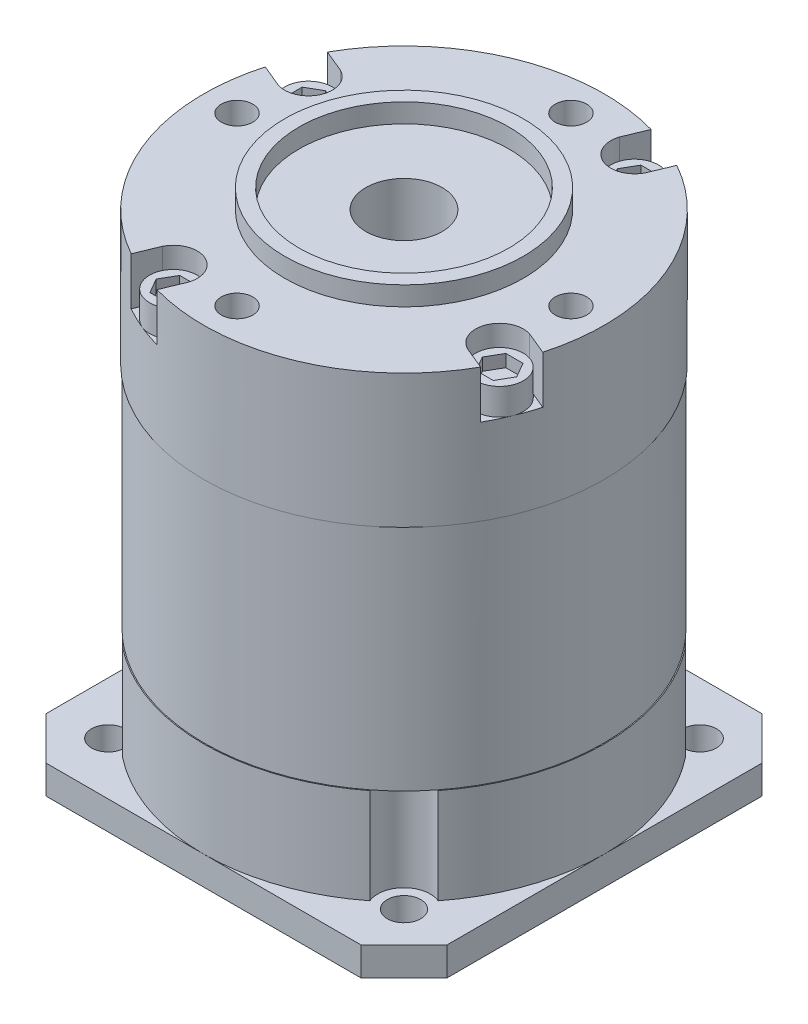
SolidWorks part; units mm, degrees
ref_plane "前视基准面" through (0, 0, 0) normal (0, 0, 1) x (1, 0, 0)
ref_plane "上视基准面" through (0, 0, 0) normal (0, 1, 0) x (1, 0, 0)
ref_plane "右视基准面" through (0, 0, 0) normal (1, 0, 0) x (0, 0, -1)
other "Configuration Table"
sketch "草图1" plane through (0, 0, 0) normal (0, 1, 0) x (1, 0, 0)
  line L1 (-21, 21) -> (21, 21)
  line L2 (-21, 21) -> (-21, -21)
  line L3 (-21, -21) -> (21, -21)
  line L4 (21, 21) -> (21, -21)
  line L5 (-21, 21) -> (21, -21) construction
  line L6 (-21, -21) -> (21, 21) construction
  point P0 (0, 0)
  dimension "D1" = 42
  dimension "D2" = 42
extrude "凸台-拉伸1" add sketch "草图1" along normal blind 3
sketch "草图2" plane through (0, 0, 0) normal (0, 1, 0) x (1, 0, 0)
  line L0 (-1000, 0) -> (49000, 0) construction
  line L1 (0, -1000) -> (0, 49000) construction
  line L2 (-21, 21) -> (-21, 16.5)
  line L3 (-21, 21) -> (-21, -21) construction
  line L4 (-21, 16.5) -> (-16.5, 21)
  line L5 (21, 21) -> (-21, 21) construction
  line L6 (-16.5, 21) -> (-21, 21)
  line L7 (16.5, 21) -> (21, 21)
  line L8 (21, 16.5) -> (16.5, 21)
  line L9 (21, 21) -> (21, 16.5)
  line L10 (21, -21) -> (21, -16.5)
  line L11 (21, -16.5) -> (16.5, -21)
  line L12 (16.5, -21) -> (21, -21)
  line L13 (-16.5, -21) -> (-21, -21)
  line L14 (-21, -16.5) -> (-16.5, -21)
  line L15 (-21, -21) -> (-21, -16.5)
  dimension "D1" = 4.5
  dimension "D2" = 4.5
extrude "切除-拉伸1" cut sketch "草图2" against normal up to surface (3 mm away) from surface at 3 up to face at (0, 0, 0) starting at face at (0, 3, 0)
sketch "草图3" plane through (0, 0, 0) normal (0, 1, 0) x (1, 0, 0)
  circle A0 centre (0, 0) radius 21
  dimension "D1" = 42
extrude "凸台-拉伸2" add sketch "草图3" along normal blind 51
sketch "草图5" plane through (0, 0, 0) normal (0, 1, 0) x (1, 0, 0)
  line L1 (-15.5, 15.5) -> (15.5, 15.5) construction
  line L2 (-15.5, 15.5) -> (-15.5, -15.5) construction
  line L3 (-15.5, -15.5) -> (15.5, -15.5) construction
  line L4 (15.5, 15.5) -> (15.5, -15.5) construction
  line L5 (-15.5, 15.5) -> (15.5, -15.5) construction
  line L6 (-15.5, -15.5) -> (15.5, 15.5) construction
  circle A0 centre (-15.5, 15.5) radius 1.75
  circle A1 centre (15.5, 15.5) radius 1.75
  circle A2 centre (-15.5, -15.5) radius 1.75
  circle A3 centre (15.5, -15.5) radius 1.75
  point P0 (0, 0)
  dimension "D3" = 3.5
  dimension "D4" = 3.5
  dimension "D5" = 3.5
  dimension "D6" = 3.5
  dimension "D1" = 31
  dimension "D2" = 31
extrude "切除-拉伸3" cut sketch "草图5" along normal up to surface (3 mm away) from surface at 0 up to face at (15.7123, 3, 15.7123) starting at face at (0, 0, 0)
sketch "草图7" plane through (0, 0, 0) normal (0, 1, 0) x (1, 0, 0)
  circle A0 centre (-15.5, 15.5) radius 2.75
  circle A1 centre (15.5, 15.5) radius 2.75
  circle A2 centre (-15.5, -15.5) radius 2.75
  circle A3 centre (15.5, -15.5) radius 2.75
  dimension "D1" = 5.5
  dimension "D2" = 5.5
  dimension "D3" = 5.5
  dimension "D4" = 5.5
extrude "切除-拉伸4" cut sketch "草图7" along normal blind 10 from surface at 3 starting at face at (15.2941, 3, -15.2941)
sketch "草图8" plane through (0, 0, 0) normal (0, 1, 0) x (1, 0, 0)
  circle A0 centre (0, 0) radius 20.9
  circle A1 centre (0, 0) radius 21
  dimension "D1" = 41.8
  dimension "D2" = 42
extrude "切除-拉伸5" cut sketch "草图8" along normal blind 24 from surface at 13 starting at face at (14.2023, 13, 14.2023)
sketch "草图9" plane through (0, 0, 0) normal (0, 1, 0) x (1, 0, 0)
  circle A0 centre (0, 0) radius 12.5
  dimension "D1" = 25
extrude "凸台-拉伸3" add sketch "草图9" along normal blind 2 from surface at 51 starting at face at (0, 51, 21)
sketch "草图11" plane through (0, 0, 0) normal (0, 1, 0) x (1, 0, 0)
  line L0 (-1000, 0) -> (49000, 0) construction
  line L1 (0, -1000) -> (0, 49000) construction
  circle A0 centre (0, 0) radius 17.5 construction
  circle A1 centre (-17.5, 0) radius 2
  circle A2 centre (0, -17.5) radius 2
  circle A3 centre (17.5, 0) radius 2
  circle A4 centre (0, 17.5) radius 2
  point P7 (0, 17.5)
  point P8 (-17.5, 0)
  point P9 (17.5, 0)
  point P10 (0, -17.5)
  point P11 (22.5067, -42.5527)
  dimension "D1" = 35
  dimension "D2" = 4
  dimension "D3" = 4
  dimension "D4" = 4
  dimension "D5" = 4
sketch "草图16" plane through (0, 0, 0) normal (0, 1, 0) x (1, 0, 0)
  circle A0 centre (0, 0) radius 11
  dimension "D1" = 22
extrude "切除-拉伸6" cut sketch "草图16" against normal up to surface (2 mm away) from surface at 53 up to face at (0, 51, 12.5) starting at face at (0, 53, 12.5)
sketch "草图17" plane through (0, 0, 0) normal (0, 1, 0) x (1, 0, 0)
  line L0 (-1000, 0) -> (49000, 0) construction
  line L1 (0, -1000) -> (0, 49000) construction
  line L2 (0, 0) -> (19134.1716, 46193.9766) construction
  line L3 (0, 0) -> (46193.9766, -19134.1716) construction
  line L4 (-18.3096, 10.2839) -> (-15.9812, 9.3194)
  line L5 (-20.2187, 5.675) -> (-17.8902, 4.7106)
  line L6 (18.3096, -10.2839) -> (15.9812, -9.3194)
  line L7 (20.2187, -5.675) -> (17.8902, -4.7106)
  line L8 (-4.7106, -17.8902) -> (-5.675, -20.2187)
  line L9 (-9.3194, -15.9812) -> (-10.2839, -18.3096)
  line L10 (4.7106, 17.8902) -> (5.675, 20.2187)
  line L11 (9.3194, 15.9812) -> (10.2839, 18.3096)
  arc A1 (-18.2024, 4.8399) -> (-16.2933, 9.4487) centre (-17.0918, 7.0796) ccw
  arc A2 (-4.8399, -18.2024) -> (-9.4487, -16.2933) centre (-7.0796, -17.0918) ccw
  arc A3 (18.2024, -4.8399) -> (16.2933, -9.4487) centre (17.0918, -7.0796) ccw
  arc A4 (4.8399, 18.2024) -> (9.4487, 16.2933) centre (7.0796, 17.0918) ccw
  circle A5 centre (0, 0) radius 21 construction
  arc A6 (-10.2839, -18.3096) -> (-5.675, -20.2187) centre (0, 0) ccw
  arc A7 (16.5312, -12.9507) -> (21, 0) centre (0, 0) ccw construction
  circle A8 centre (0, 0) radius 18.5 construction
  arc A9 (-18.3096, 10.2839) -> (-20.2187, 5.675) centre (0, 0) ccw
  arc A10 (10.2839, 18.3096) -> (5.675, 20.2187) centre (0, 0) ccw
  arc A11 (18.3096, -10.2839) -> (20.2187, -5.675) centre (0, 0) ccw
  point P12 (7.0796, 17.0918)
  point P13 (17.0918, -7.0796)
  point P14 (-7.0796, -17.0918)
  point P15 (-17.0918, 7.0796)
  dimension "D3" = 37
  dimension "D1" = 22.5
  dimension "D2" = 22.5
extrude "切除-拉伸7" cut sketch "草图17" against normal blind 5 from surface at 51 contours L6 A11 L7 A3 | L9 A6 L8 A2 | L4 A9 L5 A1 | L11 A10 L10 A4 starting at face at (0, 51, 12.5)
sketch "草图18" plane through (0, 0, 0) normal (0, 1, 0) x (1, 0, 0)
  line L1 (-15.5329, 7.9796) -> (-17.0918, 8.8796)
  line L2 (-17.0918, 8.8796) -> (-18.6506, 7.9796)
  line L3 (-18.6506, 7.9796) -> (-18.6506, 6.1796)
  line L4 (-18.6506, 6.1796) -> (-17.0918, 5.2796)
  line L5 (-17.0918, 5.2796) -> (-15.5329, 6.1796)
  line L6 (-15.5329, 6.1796) -> (-15.5329, 7.9796)
  line L7 (7.9796, 15.5329) -> (8.8796, 17.0918)
  line L8 (8.8796, 17.0918) -> (7.9796, 18.6506)
  line L9 (7.9796, 18.6506) -> (6.1796, 18.6506)
  line L10 (6.1796, 18.6506) -> (5.2796, 17.0918)
  line L11 (5.2796, 17.0918) -> (6.1796, 15.5329)
  line L12 (6.1796, 15.5329) -> (7.9796, 15.5329)
  line L13 (18.8918, -7.0796) -> (17.9918, -5.5208)
  line L14 (17.9918, -5.5208) -> (16.1918, -5.5208)
  line L15 (16.1918, -5.5208) -> (15.2918, -7.0796)
  line L16 (15.2918, -7.0796) -> (16.1918, -8.6385)
  line L17 (16.1918, -8.6385) -> (17.9918, -8.6385)
  line L18 (17.9918, -8.6385) -> (18.8918, -7.0796)
  line L19 (-6.1796, -18.6506) -> (-5.2796, -17.0918)
  line L20 (-5.2796, -17.0918) -> (-6.1796, -15.5329)
  line L21 (-6.1796, -15.5329) -> (-7.9796, -15.5329)
  line L22 (-7.9796, -15.5329) -> (-8.8796, -17.0918)
  line L23 (-8.8796, -17.0918) -> (-7.9796, -18.6506)
  line L24 (-7.9796, -18.6506) -> (-6.1796, -18.6506)
  circle A0 centre (-17.0918, 7.0796) radius 2.5
  circle A1 centre (-7.0796, -17.0918) radius 2.5
  circle A2 centre (17.0918, -7.0796) radius 2.5
  circle A3 centre (7.0796, 17.0918) radius 2.5
  circle A4 centre (-17.0918, 7.0796) radius 1.5588 construction
  circle A5 centre (7.0796, 17.0918) radius 1.5588 construction
  circle A6 centre (17.0918, -7.0796) radius 1.5588 construction
  circle A7 centre (-7.0796, -17.0918) radius 1.5588 construction
  dimension "D1" = 1.8
  dimension "D2" = 1.8
  dimension "D3" = 1.8
  dimension "D4" = 1.8
extrude "凸台-拉伸5" add sketch "草图18" along normal blind 2.8 from surface at 46 starting at face at (-7.2884, 46, 17.5958)
sketch "草图19" plane through (0, 0, 0) normal (0, 1, 0) x (1, 0, 0)
  circle A0 centre (0, 0) radius 4
  dimension "D1" = 8
extrude "切除-拉伸8" cut sketch "草图19" along normal up to surface (51 mm away) from surface at 0 up to face at (0, 51, 11) starting at face at (15.5, 0, -13.75)
sketch "草图20" plane through (0, 0, 0) normal (0, 1, 0) x (1, 0, 0)
  line L0 (7.9796, 18.6506) -> (6.1796, 18.6506) construction
  line L1 (6.1796, 18.6506) -> (5.2796, 17.0918) construction
  line L2 (5.2796, 17.0918) -> (6.1796, 15.5329) construction
  line L3 (6.1796, 15.5329) -> (7.9796, 15.5329) construction
  line L4 (7.9796, 15.5329) -> (8.8796, 17.0918) construction
  line L5 (8.8796, 17.0918) -> (7.9796, 18.6506) construction
  line L6 (16.1918, -5.5208) -> (15.2918, -7.0796) construction
  line L7 (15.2918, -7.0796) -> (16.1918, -8.6385) construction
  line L8 (16.1918, -8.6385) -> (17.9918, -8.6385) construction
  line L9 (17.9918, -8.6385) -> (18.8918, -7.0796) construction
  line L10 (18.8918, -7.0796) -> (17.9918, -5.5208) construction
  line L11 (17.9918, -5.5208) -> (16.1918, -5.5208) construction
  line L12 (-6.1796, -15.5329) -> (-7.9796, -15.5329) construction
  line L13 (-7.9796, -15.5329) -> (-8.8796, -17.0918) construction
  line L14 (-8.8796, -17.0918) -> (-7.9796, -18.6506) construction
  line L15 (-7.9796, -18.6506) -> (-6.1796, -18.6506) construction
  line L16 (-6.1796, -18.6506) -> (-5.2796, -17.0918) construction
  line L17 (-5.2796, -17.0918) -> (-6.1796, -15.5329) construction
  line L18 (-18.6506, 7.9796) -> (-18.6506, 6.1796) construction
  line L19 (-18.6506, 6.1796) -> (-17.0918, 5.2796) construction
  line L20 (-17.0918, 5.2796) -> (-15.5329, 6.1796) construction
  line L21 (-15.5329, 6.1796) -> (-15.5329, 7.9796) construction
  line L22 (-15.5329, 7.9796) -> (-17.0918, 8.8796) construction
  line L23 (-17.0918, 8.8796) -> (-18.6506, 7.9796) construction
  line L24 (7.9796, 18.6506) -> (6.1796, 18.6506)
  line L25 (6.1796, 18.6506) -> (5.2796, 17.0918)
  line L26 (5.2796, 17.0918) -> (6.1796, 15.5329)
  line L27 (6.1796, 15.5329) -> (7.9796, 15.5329)
  line L28 (7.9796, 15.5329) -> (8.8796, 17.0918)
  line L29 (8.8796, 17.0918) -> (7.9796, 18.6506)
  line L30 (16.1918, -5.5208) -> (15.2918, -7.0796)
  line L31 (15.2918, -7.0796) -> (16.1918, -8.6385)
  line L32 (16.1918, -8.6385) -> (17.9918, -8.6385)
  line L33 (17.9918, -8.6385) -> (18.8918, -7.0796)
  line L34 (18.8918, -7.0796) -> (17.9918, -5.5208)
  line L35 (17.9918, -5.5208) -> (16.1918, -5.5208)
  line L36 (-6.1796, -15.5329) -> (-7.9796, -15.5329)
  line L37 (-7.9796, -15.5329) -> (-8.8796, -17.0918)
  line L38 (-8.8796, -17.0918) -> (-7.9796, -18.6506)
  line L39 (-7.9796, -18.6506) -> (-6.1796, -18.6506)
  line L40 (-6.1796, -18.6506) -> (-5.2796, -17.0918)
  line L41 (-5.2796, -17.0918) -> (-6.1796, -15.5329)
  line L42 (-18.6506, 7.9796) -> (-18.6506, 6.1796)
  line L43 (-18.6506, 6.1796) -> (-17.0918, 5.2796)
  line L44 (-17.0918, 5.2796) -> (-15.5329, 6.1796)
  line L45 (-15.5329, 6.1796) -> (-15.5329, 7.9796)
  line L46 (-15.5329, 7.9796) -> (-17.0918, 8.8796)
  line L47 (-17.0918, 8.8796) -> (-18.6506, 7.9796)
extrude "凸台-拉伸6" add sketch "草图20" along normal blind 1.5 from surface at 46 starting at face at (-17.0918, 46, -7.0796)
sketch "草图21" plane through (0, 0, 0) normal (0, 1, 0) x (1, 0, 0)
  circle A0 centre (0, 0) radius 12.5
  dimension "D1" = 25
extrude "切除-拉伸9" cut sketch "草图21" along normal blind 3
hole_wizard "M4 螺纹孔1" positions "草图24" profile "草图25" tap size "M4" standard "ISO"
sketch "草图24" plane through (0, 51, 0) normal (0, 1, 0) x (1, 0, 0)
  point P0 (0, 17.5)
  point P3 (-17.5, 0)
  point P6 (17.5, 0)
  point P9 (0, -17.5)
sketch "草图25" plane through (0, 51, -17.5) normal (1, 0, 0) x (0, 0, 1)
  line L0 (0, 0) -> (0, 11.0914)
  line L1 (0, 11.0914) -> (1.65, 10.1)
  line L2 (1.65, 10.1) -> (1.65, 0)
  line L5 (1.65, 0) -> (0, 0)
  line L10 (0, 11.0914) -> (-1.65, 10.1) construction
  line L11 (0, -6.35) -> (0, 107.95) construction
  dimension "螺纹孔钻头直径" = 3.3
  dimension "螺纹孔钻头深度" = 10.1
  dimension "导头角度" = 118
cosmetic thread "孔螺蚊线1" parameters "D1"=8, "D2"=4
cosmetic thread "孔螺蚊线2" parameters "D1"=8, "D2"=4
cosmetic thread "孔螺蚊线3" parameters "D1"=8, "D2"=4
cosmetic thread "孔螺蚊线4" parameters "D1"=8, "D2"=4
